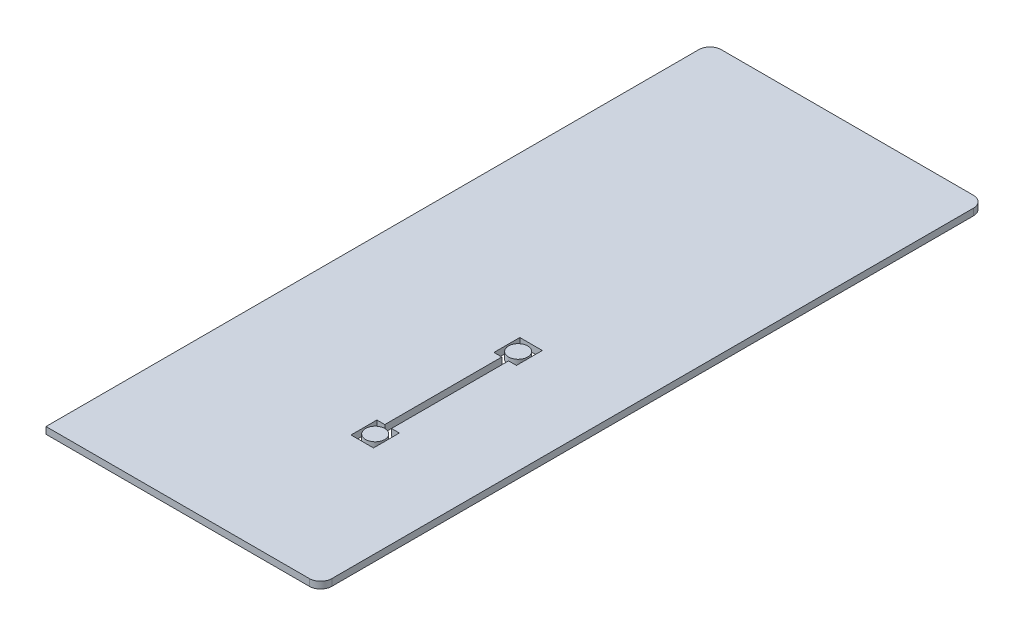
SolidWorks part; units mm, degrees
ref_plane "Front Plane" through (0, 0, 0) normal (0, 0, 1) x (1, 0, 0)
ref_plane "Top Plane" through (0, 0, 0) normal (0, 1, 0) x (1, 0, 0)
ref_plane "Right Plane" through (0, 0, 0) normal (1, 0, 0) x (0, 0, -1)
sketch "Sketch1" plane through (0, 0, 0) normal (0, 1, 0) x (1, 0, 0)
  line L1 (0, 0) -> (122, 0)
  line L2 (0, 0) -> (0, 295)
  line L3 (0, 295) -> (122, 295)
  line L4 (122, 0) -> (122, 295)
  dimension "D1" = 295
  dimension "D2" = 122
extrude "Boss-Extrude1" add sketch "Sketch1" along normal blind 3
fillet "Fillet1" radius 5 3 edges at (0, 1.5, -295) (122, 1.5, -295) (122, 1.5, 0)
sketch "Sketch2" plane through (0, 3, 0) normal (0, 1, 0) x (1, 0, 0)
  line L0 (71, 139.5) -> (81, 139.5)
  line L1 (81, 139.5) -> (81, 128)
  line L2 (81, 128) -> (77.5, 128)
  line L3 (77.5, 128) -> (77.5, 76)
  line L4 (77.5, 76) -> (81, 76)
  line L5 (81, 76) -> (81, 64.5)
  line L6 (81, 64.5) -> (71, 64.5)
  line L7 (71, 64.5) -> (71, 76)
  line L8 (71, 76) -> (74.5, 76)
  line L9 (74.5, 76) -> (74.5, 128)
  line L10 (74.5, 128) -> (71, 128)
  line L11 (71, 128) -> (71, 139.5)
  circle A0 centre (76, 133.75) radius 4.25
  circle A1 centre (76, 70.25) radius 4.25
  dimension "D1" = 8.5
  dimension "D2" = 8.5
extrude "Cut-Extrude1" cut sketch "Sketch2" against normal blind 3
